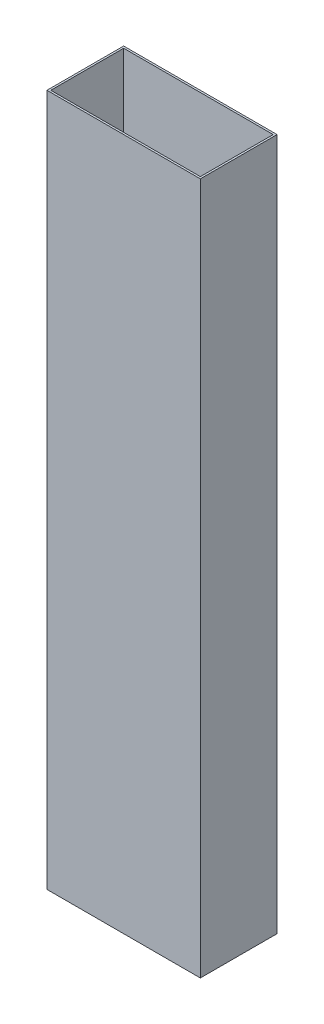
SolidWorks part; units mm, degrees
ref_plane "Front Plane" through (0, 0, 0) normal (0, 0, 1) x (1, 0, 0)
ref_plane "Top Plane" through (0, 0, 0) normal (0, 1, 0) x (1, 0, 0)
ref_plane "Right Plane" through (0, 0, 0) normal (1, 0, 0) x (0, 0, -1)
sketch "Sketch1" plane through (0, 0, 0) normal (0, 1, 0) x (1, 0, 0)
  line L1 (101.6, 50.8) -> (-101.6, 50.8)
  line L2 (101.6, 50.8) -> (101.6, -50.8)
  line L3 (101.6, -50.8) -> (-101.6, -50.8)
  line L4 (-101.6, 50.8) -> (-101.6, -50.8)
  line L5 (101.6, 50.8) -> (-101.6, -50.8) construction
  line L6 (101.6, -50.8) -> (-101.6, 50.8) construction
  line L7 (99.06, -48.26) -> (-99.06, -48.26)
  line L8 (99.06, -48.26) -> (99.06, 48.26)
  line L9 (99.06, 48.26) -> (-99.06, 48.26)
  line L10 (-99.06, -48.26) -> (-99.06, 48.26)
  line L11 (99.06, -48.26) -> (-99.06, 48.26) construction
  line L12 (99.06, 48.26) -> (-99.06, -48.26) construction
  point P0 (0, 0)
  point P6 (0, 0)
  dimension "D1" = 101.6
  dimension "D2" = 203.2
  dimension "D3" = 2.54
  dimension "D4" = 2.54
extrude "Boss-Extrude1" add sketch "Sketch1" against normal blind 1526.54 contours L1 L4 L3 L2
sketch "Sketch2" plane through (101.6, 0, 0) normal (1, 0, 0) x (0, 0, -1)
  line L0 (50.8, -1526.54) -> (50.8, 0) construction
  line L1 (-50.8, -1526.54) -> (48.26, -1526.54)
  line L2 (-50.8, -1526.54) -> (-50.8, -916.94)
  line L3 (-50.8, -916.94) -> (48.26, -916.94)
  line L4 (48.26, -1526.54) -> (48.26, -916.94)
  dimension "D1" = 2.54
  dimension "D2" = 609.6
extrude "Cut-Extrude1" cut sketch "Sketch2" against normal through all
sketch "Sketch3" plane through (0, 0, -48.26) normal (0, 0, 1) x (1, 0, 0)
  line L0 (101.6, -1526.54) -> (101.6, -916.94) construction
  line L1 (-101.6, -1526.54) -> (101.6, -1526.54)
  line L2 (-101.6, -1526.54) -> (-101.6, -1524)
  line L3 (-101.6, -1524) -> (101.6, -1524)
  line L4 (101.6, -1526.54) -> (101.6, -1524)
  dimension "D1" = 2.54
extrude "Boss-Extrude2" add sketch "Sketch3" along normal blind 101.6
sketch "Sketch4" plane through (-101.6, 0, 0) normal (-1, 0, 0) x (0, 0, 1)
  line L0 (-48.26, -916.94) -> (-50.8, -916.94)
  line L1 (-50.8, -1526.54) -> (-50.8, 0) construction
  line L2 (-50.8, -916.94) -> (-50.8, -1526.54)
  line L3 (-48.26, -1524) -> (-48.26, -916.94) construction
  line L4 (53.34, -1524) -> (-48.26, -1524) construction
  line L5 (-50.8, -1526.54) -> (53.34, -1526.54) construction
  line L6 (-48.26, -1524) -> (-48.26, -916.94)
  line L7 (53.34, -1524) -> (-48.26, -1524)
  line L8 (-50.8, -1526.54) -> (53.34, -1526.54)
  line L9 (53.34, -1524) -> (53.34, -1526.54)
extrude "Cut-Extrude2" cut sketch "Sketch4" against normal through all
